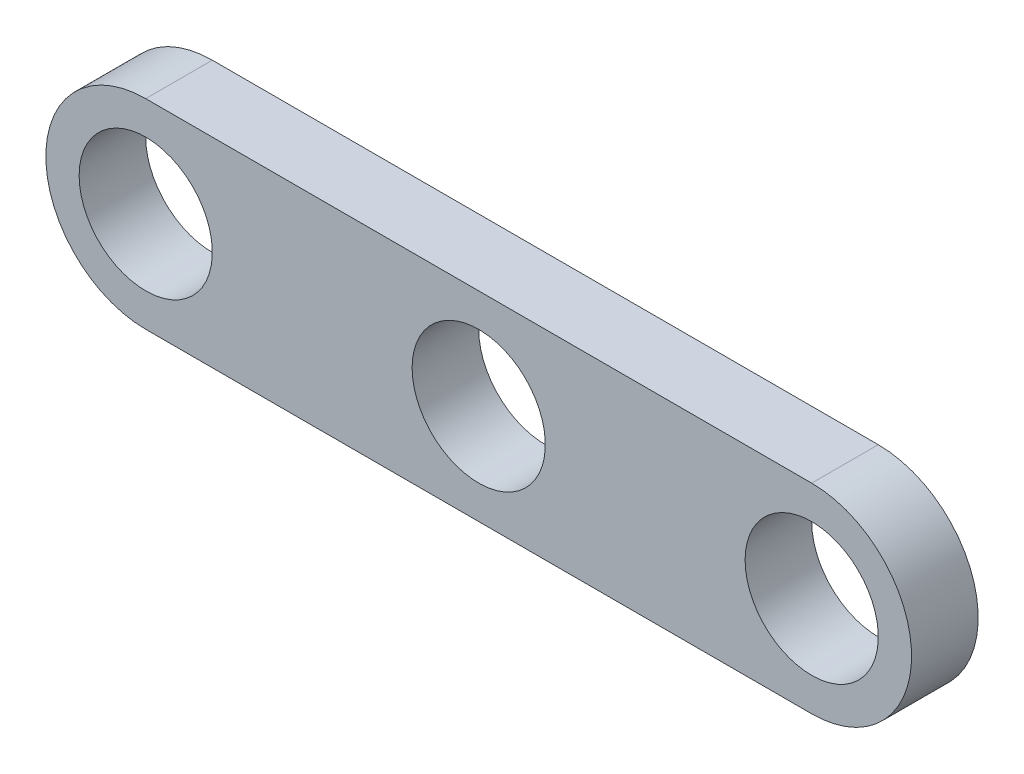
SolidWorks part; units mm, degrees
ref_plane "Спереди" through (0, 0, 0) normal (0, 0, 1) x (1, 0, 0)
ref_plane "Сверху" through (0, 0, 0) normal (0, 1, 0) x (1, 0, 0)
ref_plane "Справа" through (0, 0, 0) normal (1, 0, 0) x (0, 0, -1)
sketch "Эскиз1" plane through (0, 0, 0) normal (0, 0, 1) x (1, 0, 0)
  line L0 (0, 0) -> (-100, 0)
  line L1 (0, 30) -> (-100, 30)
  arc A0 (0, 0) -> (0, 30) centre (0, 15) ccw
  arc A1 (-100, 30) -> (-100, 0) centre (-100, 15) ccw
  point P5 (0, 0)
  dimension "D1" = 100
  dimension "D2" = 30
extrude "Бобышка-Вытянуть2" add sketch "Эскиз1" along normal blind 10 contours A1 L0 A0 L1
sketch "Эскиз2" plane through (0, 0, 0) normal (0, 0, -1) x (-1, 0, 0)
  circle A0 centre (0, 15) radius 10
  circle A1 centre (100, 15) radius 10
  dimension "D1" = 20
  dimension "D2" = 20
extrude "Вырез-Вытянуть1" cut sketch "Эскиз2" against normal blind 10
sketch "Эскиз3" plane through (0, 0, 0) normal (0, 0, -1) x (-1, 0, 0)
  circle A0 centre (50, 15) radius 10
  point P2 (0, 0)
  dimension "D1" = 50
extrude "Вырез-Вытянуть2" cut sketch "Эскиз3" against normal blind 10
